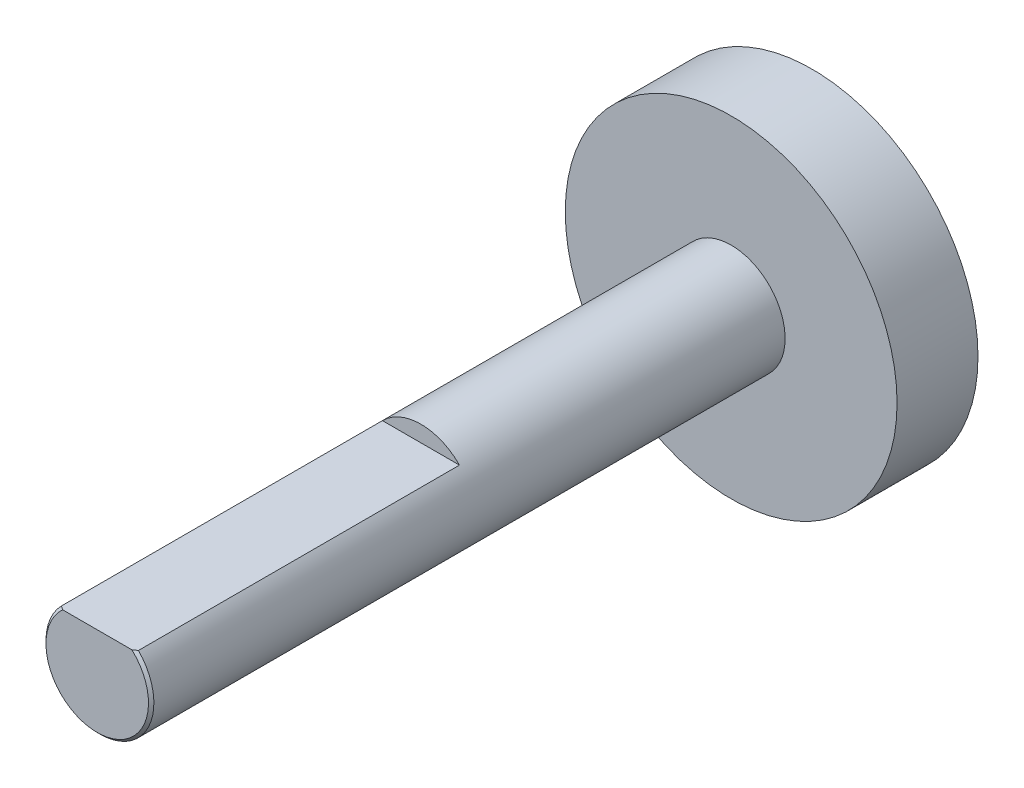
SolidWorks part; units mm, degrees
material "Chrome Stainless Steel"
ref_plane "Front Plane" through (0, 0, 0) normal (0, 0, 1) x (1, 0, 0)
ref_plane "Top Plane" through (0, 0, 0) normal (0, 1, 0) x (1, 0, 0)
ref_plane "Right Plane" through (0, 0, 0) normal (1, 0, 0) x (0, 0, -1)
sketch "Sketch1" plane through (0, 0, 0) normal (0, 0, 1) x (1, 0, 0)
  circle A0 centre (0, 0) radius 2
  dimension "D1" = 4
extrude "Boss-Extrude1" add sketch "Sketch1" against normal blind 26.5
sketch "Sketch2" plane through (0, 0, -26.5) normal (0, 0, -1) x (-1, 0, 0)
  circle A0 centre (0, 0) radius 6.15
  dimension "D1" = 12.3
extrude "Boss-Extrude2" add sketch "Sketch2" against normal blind 3
sketch "Sketch3" plane through (0, 0, 0) normal (0, 0, 1) x (1, 0, 0)
  line L0 (0, -2) -> (0, 1.4) construction
  line L1 (0, 1.4) -> (1.4283, 1.4) construction
  line L2 (1.4283, 1.4) -> (-1.4283, 1.4)
  circle A0 centre (0, 0) radius 2 construction
  circle A1 centre (0, 0) radius 2 construction
  arc A2 (1.4283, 1.4) -> (-1.4283, 1.4) centre (0, 0) ccw
  dimension "D1" = 4
  dimension "D2" = 3.4
chamfer "Chamfer1" distance 0.1 angle 45 1 edges at (2, 0, 0)
extrude "Cut-Extrude2" cut sketch "Sketch3" against normal blind 12
